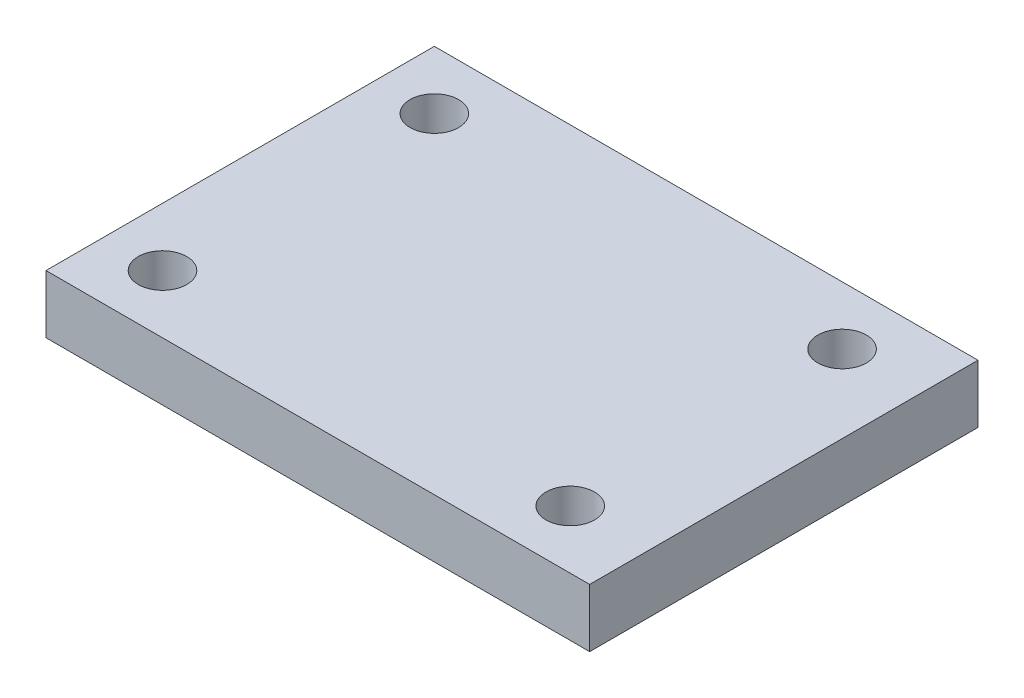
SolidWorks part; units mm, degrees
ref_plane "Front Plane" through (0, 0, 0) normal (0, 0, 1) x (1, 0, 0)
ref_plane "Top Plane" through (0, 0, 0) normal (0, 1, 0) x (1, 0, 0)
ref_plane "Right Plane" through (0, 0, 0) normal (1, 0, 0) x (0, 0, -1)
sketch "Sketch1" plane through (0, 0, 0) normal (0, 1, 0) x (1, 0, 0)
  line L1 (-14, 10) -> (14, 10)
  line L2 (-14, 10) -> (-14, -10)
  line L3 (-14, -10) -> (14, -10)
  line L4 (14, 10) -> (14, -10)
  line L5 (-14, 10) -> (14, -10) construction
  line L6 (-14, -10) -> (14, 10) construction
  point P0 (0, 0)
  dimension "D1" = 20
  dimension "D2" = 28
extrude "Boss-Extrude1" add sketch "Sketch1" along normal blind 3
hole_wizard "M3 Tapped Hole1" positions "Sketch2" profile "Sketch3" tap size "M3" standard "DIN" end condition through all
sketch "Sketch2" plane through (0, 3, 0) normal (0, 1, 0) x (1, 0, 0)
  line L0 (-14, 10) -> (-14, -10) construction
  line L1 (14, 10) -> (-14, 10) construction
  point P0 (-11, 7)
  point P2 (-11, -7)
  point P4 (10, -7)
  point P6 (10, 7)
  dimension "D1" = 14
  dimension "D2" = 21
  dimension "D3" = 3
  dimension "D4" = 3
sketch "Sketch3" plane through (-11, 3, -7) normal (1, 0, 0) x (0, 0, 1)
  line L0 (0, 0) -> (0, 3)
  line L1 (0, 3) -> (1.25, 3)
  line L2 (1.25, 3) -> (1.25, 0)
  line L5 (1.25, 0) -> (0, 0)
  line L11 (0, -6.35) -> (0, 107.95) construction
  dimension "Thru Tap Drill Dia." = 2.5
  dimension "Thru Tap Drill Depth" = 3
cosmetic thread "Hole Thread1" parameters "D2"=3
cosmetic thread "Hole Thread2" parameters "D2"=3
cosmetic thread "Hole Thread3" parameters "D2"=3
cosmetic thread "Hole Thread4" parameters "D2"=3
